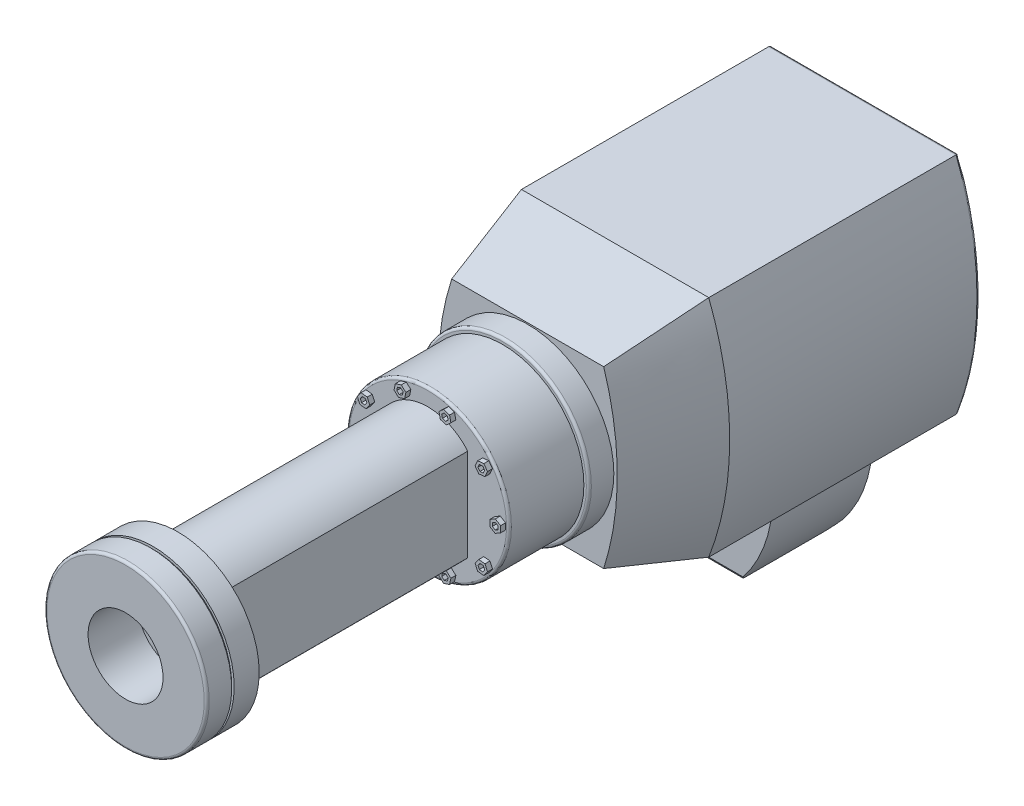
SolidWorks part; units mm, degrees
ref_plane "Front Plane" through (0, 0, 0) normal (0, 0, 1) x (1, 0, 0)
ref_plane "Top Plane" through (0, 0, 0) normal (0, 1, 0) x (1, 0, 0)
ref_plane "Right Plane" through (0, 0, 0) normal (1, 0, 0) x (0, 0, -1)
sketch "Sketch1" plane through (0, 0, 0) normal (0, 0, 1) x (1, 0, 0)
  line L0 (0, 45) -> (0, -45) construction
  line L1 (37.5, 45) -> (-37.5, 45)
  line L2 (37.5, -45) -> (-37.5, -45)
  arc A0 (-37.5, 45) -> (-37.5, -45) centre (79.119, 0) ccw
  arc A1 (37.5, 45) -> (37.5, -45) centre (-79.119, 0) cw
  point P4 (0, 0)
  point P8 (0, 45)
  point P10 (0, -45)
  dimension "D3" = 125
  dimension "D1" = 90
  dimension "D2" = 75
extrude "Boss-Extrude1" add sketch "Sketch1" along normal blind 100
sketch "Sketch2" plane through (0, 0, 100) normal (0, 0, 1) x (1, 0, 0)
  line L2 (37.5, 45) -> (-37.5, 45)
  line L3 (-37.5, -45) -> (37.5, -45)
  line L4 (37.5, 45) -> (-37.5, 45)
  line L5 (-37.5, -45) -> (37.5, -45)
  arc A2 (37.5, -45) -> (37.5, 45) centre (-79.119, 0) ccw
  arc A3 (-37.5, 45) -> (-37.5, -45) centre (79.119, 0) ccw
  arc A4 (37.5, -45) -> (37.5, 45) centre (-79.119, 0) ccw
  arc A5 (-37.5, 45) -> (-37.5, -45) centre (79.119, 0) ccw
  dimension "D1" = 0
ref_plane "Plane1" through (0, 0, 135) normal (0, 0, 1) x (1, 0, 0)
sketch "Sketch3" plane through (0, 0, 135) normal (0, 0, 1) x (1, 0, 0)
  line L4 (30.4255, 35) -> (-30.4255, 35)
  line L5 (-30.4255, -35) -> (30.4255, -35)
  line L6 (30.4255, 35) -> (-30.4255, 35)
  line L7 (-30.4255, -35) -> (30.4255, -35)
  arc A4 (-30.4255, 35) -> (-30.4255, -35) centre (79.119, 0) ccw
  arc A5 (30.4255, -35) -> (30.4255, 35) centre (-79.119, 0) ccw
  arc A6 (-30.4255, 35) -> (-30.4255, -35) centre (79.119, 0) ccw
  arc A7 (30.4255, -35) -> (30.4255, 35) centre (-79.119, 0) ccw
  dimension "D1" = 10
loft "Loft1" add profiles "Sketch3", "Sketch2"
sketch "Sketch4" plane through (0, 0, 135) normal (0, 0, 1) x (1, 0, 0)
  circle A0 centre (0, 0) radius 34.5
  dimension "D1" = 69
extrude "Boss-Extrude2" add sketch "Sketch4" along normal blind 10
sketch "Sketch5" plane through (0, 0, 145) normal (0, 0, 1) x (1, 0, 0)
  circle A2 centre (0, 0) radius 32.5
  circle A3 centre (0, 0) radius 32.5
  dimension "D1" = 2
extrude "Boss-Extrude3" add sketch "Sketch5" along normal blind 30
sketch "Sketch6" plane through (0, 0, 175) normal (0, 0, 1) x (1, 0, 0)
  line L0 (0, 0) -> (29, 0) construction
  line L1 (30.1651, 0.6726) -> (29, 1.3453)
  line L2 (29, -2.5) -> (31.1651, -1.25)
  line L3 (31.1651, -1.25) -> (31.1651, 1.25)
  line L4 (31.1651, 1.25) -> (29, 2.5)
  line L5 (29, 2.5) -> (26.8349, 1.25)
  line L6 (26.8349, 1.25) -> (26.8349, -1.25)
  line L7 (26.8349, -1.25) -> (29, -2.5)
  line L8 (29, 1.3453) -> (27.8349, 0.6726)
  line L9 (27.8349, 0.6726) -> (27.8349, -0.6726)
  line L10 (27.8349, -0.6726) -> (29, -1.3453)
  line L11 (29, -1.3453) -> (30.1651, -0.6726)
  line L12 (30.1651, -0.6726) -> (30.1651, 0.6726)
  circle A0 centre (29, 0) radius 2.1651 construction
  dimension "D1" = 29
  dimension "D2" = 5
  dimension "D3" = 1
extrude "Boss-Extrude4" add sketch "Sketch6" along normal blind 2
pattern_circular "CirPattern1" count 10 over 360 about axis through (-0.1426, 0, 0) along (0, 0, 1) of "Boss-Extrude4"
sketch "Sketch9" plane through (0, 0, 175) normal (0, 0, 1) x (1, 0, 0)
  line L0 (0, 0) -> (16, 0) construction
  line L1 (16, 18.5) -> (16, -18.5)
  line L2 (0, 28.413) -> (0, -28.413) construction
  line L3 (-16, 18.5) -> (-16, -18.5)
  arc A0 (-16, 18.5) -> (16, 18.5) centre (0, 4.8985) cw
  arc A1 (-16, -18.5) -> (16, -18.5) centre (0, -4.8985) ccw
  point P6 (16, 0)
  point P9 (0, 0)
  dimension "D3" = 21
  dimension "D1" = 16
  dimension "D2" = 37
extrude "Boss-Extrude5" add sketch "Sketch9" along normal blind 100
sketch "Sketch11" plane through (0, 0, 275) normal (0, 0, 1) x (1, 0, 0)
  circle A0 centre (0, 0) radius 32.5 construction
  circle A1 centre (0, 0) radius 32.5
extrude "Boss-Extrude6" add sketch "Sketch11" along normal blind 10
sketch "Sketch12" plane through (0, 0, 285) normal (0, 0, 1) x (1, 0, 0)
  circle A2 centre (0, 0) radius 31.5
  circle A3 centre (0, 0) radius 31.5
  dimension "D1" = 1
extrude "Boss-Extrude7" add sketch "Sketch12" along normal blind 1
sketch "Sketch13" plane through (0, 0, 286) normal (0, 0, 1) x (1, 0, 0)
  circle A0 centre (0, 0) radius 32.5 construction
  circle A1 centre (0, 0) radius 32.5
extrude "Boss-Extrude8" add sketch "Sketch13" along normal blind 10
ref_plane "Plane2" through (-37.5, 0, 0) normal (1, 0, 0) x (0, 0, -1)
sketch "Sketch14" plane through (-37.5, 0, 0) normal (1, 0, 0) x (0, 0, -1)
  line L0 (-100, -45) -> (0, -45) construction
  circle A0 centre (-50, -45) radius 42.5
extrude "Boss-Extrude9" add sketch "Sketch14" along normal mid plane 21
sketch "Sketch15" plane through (-27, 0, 0) normal (1, 0, 0) x (0, 0, -1)
  line L0 (-50, -45) -> (-50, -75) construction
  line L1 (-92.5, -45) -> (-7.5, -45) construction
  line L2 (-70, -45) -> (-70, -75)
  line L3 (-30, -45) -> (-30, -75)
  line L4 (-70, -45) -> (-30, -45)
  arc A0 (-70, -75) -> (-30, -75) centre (-50, -60.3189) ccw
  dimension "D4" = 24.81
  dimension "D1" = 30
  dimension "D2" = 20
  dimension "D3" = 20
extrude "Boss-Extrude10" add sketch "Sketch15" along normal blind 35
ref_plane "Plane3" through (0, 0, 50) normal (0, 0, 1) x (1, 0, 0)
sketch "Sketch16" plane through (0, 0, 50) normal (0, 0, 1) x (1, 0, 0)
  line L0 (8, -45) -> (8, -87)
  line L1 (8, -45) -> (33, -45)
  line L2 (-37.5, -45) -> (37.5, -45) construction
  arc A0 (33, -45) -> (8, -87) centre (-21.8393, -40.7981) cw
  dimension "D3" = 55
  dimension "D1" = 25
  dimension "D2" = 42
extrude "Boss-Extrude11" add sketch "Sketch16" along normal mid plane 40
sketch "Sketch17" plane through (8, 0, 0) normal (-1, 0, 0) x (0, 0, 1)
  line L3 (70, -87) -> (70, -75)
  line L4 (30, -75) -> (30, -87)
  line L5 (30, -87) -> (70, -87)
  line L6 (70, -87) -> (70, -75)
  line L7 (30, -75) -> (30, -87)
  line L8 (30, -87) -> (70, -87)
  arc A1 (30, -75) -> (70, -75) centre (50, -60.3189) ccw
  arc A2 (30, -75) -> (70, -75) centre (50, -60.3189) ccw
  dimension "D1" = 0
extrude "Cut-Extrude1" cut sketch "Sketch17" against normal through all
fillet "Fillet1" radius 1 9 edges at (0, 45, 0) (-45.881, 0, 0) (0, -45, 0) (45.881, 0, 0) (32.5, 0, 296) (32.5, 0, 175) (34.5, 0, 145) (-48, -45, 7.5) (-27, -87.5, 50)
sketch "Sketch18" plane through (0, 0, 296) normal (0, 0, 1) x (1, 0, 0)
  circle A0 centre (0, 0) radius 15
  dimension "D1" = 30
extrude "Cut-Extrude2" cut sketch "Sketch18" against normal blind 20
sketch "Sketch19" plane through (-48, 0, 0) normal (-1, 0, 0) x (0, 0, 1)
  circle A0 centre (50, -45) radius 15
  dimension "D1" = 30
extrude "Cut-Extrude3" cut sketch "Sketch19" against normal blind 20
